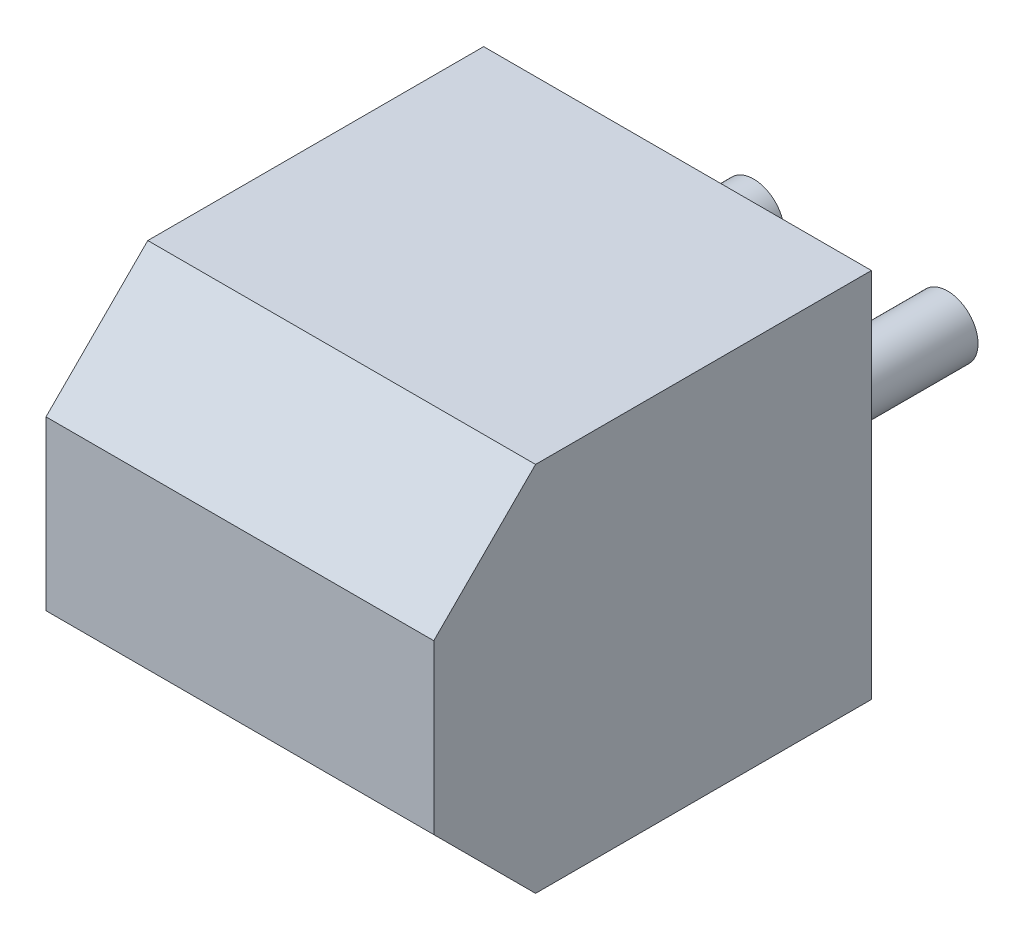
SolidWorks part; units mm, degrees
ref_plane "前视基准面" through (0, 0, 0) normal (0, 0, 1) x (1, 0, 0)
ref_plane "上视基准面" through (0, 0, 0) normal (0, 1, 0) x (1, 0, 0)
ref_plane "右视基准面" through (0, 0, 0) normal (1, 0, 0) x (0, 0, -1)
sketch "草图1" plane through (0, 0, 0) normal (0, 0, 1) x (1, 0, 0)
  line L1 (0, 0) -> (7.62, 0)
  line L2 (0, 0) -> (0, 7.3)
  line L3 (0, 7.3) -> (7.62, 7.3)
  line L4 (7.62, 0) -> (7.62, 7.3)
  dimension "D1" = 7.62
  dimension "D2" = 7.3
extrude "凸台-拉伸1" add sketch "草图1" along normal blind 8.6
chamfer "倒角1" distance 2 angle 45 2 edges at (3.81, 0, 8.6) (3.81, 7.3, 8.6)
sketch "草图2" plane through (0, 0, 0) normal (0, -1, 0) x (1, 0, 0)
  line L1 (1.155, 4.7244) -> (2.655, 4.7244)
  line L2 (1.155, 4.7244) -> (1.155, 2.4797)
  line L3 (1.155, 2.4797) -> (2.655, 2.4797)
  line L4 (2.655, 4.7244) -> (2.655, 2.4797)
  line L5 (3.81, 0) -> (3.81, 12.0535) construction
  line L6 (0, 0) -> (7.62, 0) construction
  line L7 (1.905, 4.7244) -> (1.905, 1.5061) construction
  dimension "D1" = 1.905
  dimension "D2" = 1.5
extrude "切除-拉伸1" cut sketch "草图2" against normal blind 0.5
pattern_linear "阵列(线性)1" count 2 spacing 3.81 along (1, 0, 0) of "切除-拉伸1"
sketch "草图3" plane through (0, 0, 0) normal (0, 0, -1) x (-1, 0, 0)
  line L0 (-7.62, 3.7) -> (2.0184, 3.7) construction
  line L1 (-7.62, 0) -> (-7.62, 7.3) construction
  line L2 (-7.62, 7.3) -> (0, 7.3) construction
  line L3 (-3.81, 7.3) -> (-3.81, -1.5587) construction
  circle A0 centre (-5.715, 3.7) radius 0.6
  dimension "D2" = 1.2
  dimension "D1" = 3.6
  dimension "D3" = 1.905
extrude "凸台-拉伸2" add sketch "草图3" along normal blind 3.4
pattern_linear "阵列(线性)2" count 2 spacing 3.81 along (-1, 0, 0) of "凸台-拉伸2"
